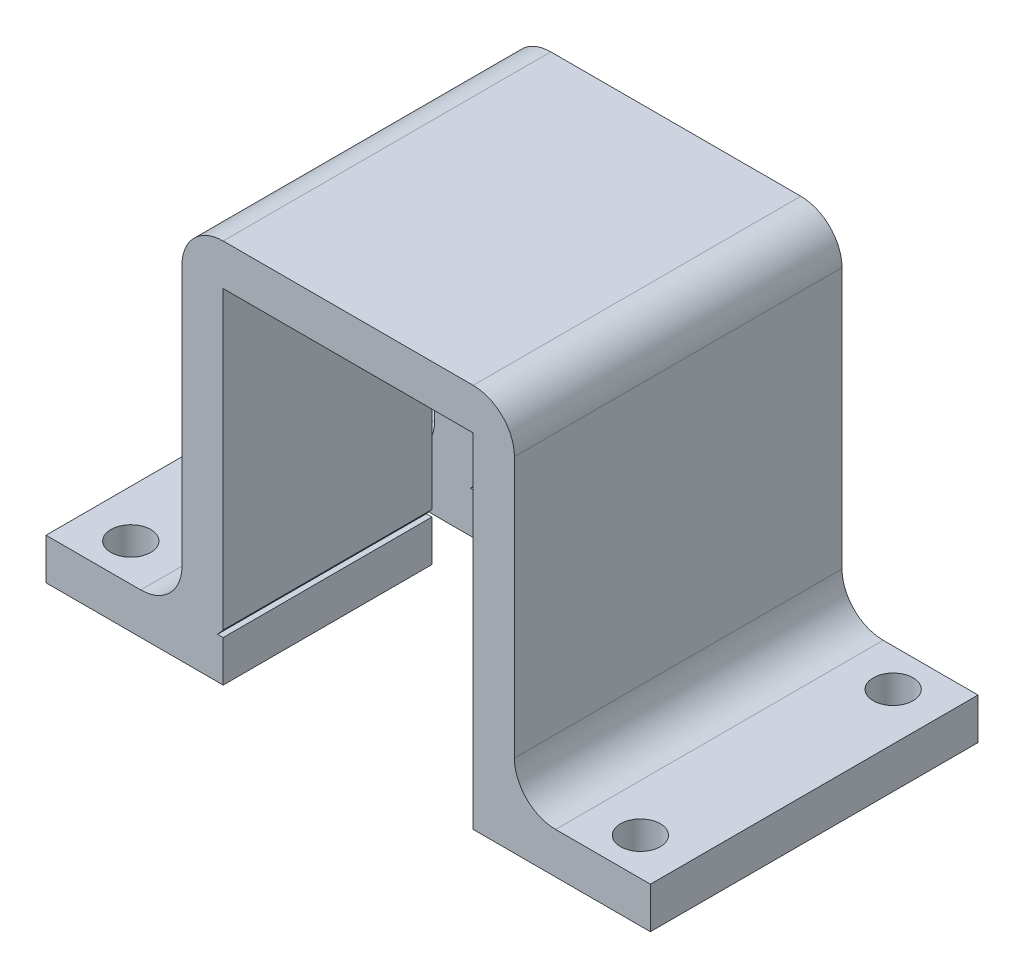
SolidWorks part; units mm, degrees
ref_plane "Front Plane" through (0, 0, 0) normal (0, 0, 1) x (1, 0, 0)
ref_plane "Top Plane" through (0, 0, 0) normal (0, 1, 0) x (1, 0, 0)
ref_plane "Right Plane" through (0, 0, 0) normal (1, 0, 0) x (0, 0, -1)
sketch "Sketch1" plane through (0, 0, 0) normal (0, 0, 1) x (1, 0, 0)
  line L1 (-9.1, 11) -> (9.1, 11)
  line L2 (-9.1, 11) -> (-9.1, -11)
  line L4 (9.1, 11) -> (9.1, -11)
  line L7 (-9.1, 14) -> (9.1, 14)
  line L8 (-12.1, 11) -> (-12.1, -8)
  line L9 (-12.1, -14) -> (-9.1, -14)
  line L10 (12.1, 11) -> (12.1, -8)
  line L12 (-9.1, -11) -> (-9.1, -14)
  line L13 (-22, -11) -> (-15.1, -11)
  line L14 (-22, -11) -> (-22, -14)
  line L15 (-22, -14) -> (-9.1, -14)
  line L16 (22, -11) -> (22, -14)
  line L17 (9.1, -11) -> (9.1, -14)
  line L18 (9.1, -14) -> (12.1, -14)
  line L19 (-9.5071, -11) -> (-9.1, -11)
  line L20 (-9.5071, -11) -> (-9.1, -10.5289) construction
  line L21 (15.1, -11) -> (22, -11)
  line L22 (9.1, -14) -> (22, -14)
  arc A0 (-9.1, 14) -> (-12.1, 11) centre (-9.1, 11) ccw
  arc A1 (9.1, 14) -> (12.1, 11) centre (9.1, 11) cw
  arc A2 (-12.1, -8) -> (-15.1, -11) centre (-15.1, -8) cw
  arc A3 (12.1, -8) -> (15.1, -11) centre (15.1, -8) ccw
  point P0 (0, 0)
  point P6 (0, 0)
  point P17 (0, -12.5)
  dimension "D5" = 3
  dimension "D9" = 3
  dimension "D1" = 22
  dimension "D2" = 18.2
  dimension "D3" = 3
  dimension "D4" = 3
  dimension "D6" = 3
  dimension "D7" = 44
  dimension "D8" = 14
  dimension "D10" = 3
  dimension "D11" = 9.9
  dimension "D12" = 9.9
  dimension "D13" = 9.1
  dimension "D14" = 9.1
extrude "Boss-Extrude1" add sketch "Sketch1" along normal blind 23.85 contours L19 L20 L2 L1 L4 L17 L18 L22 L16 L21 A3 L10 A1 L7 A0 L8 A2 L13 L14 L15 L9 L12
sketch "Sketch4" plane through (0, -11, 0) normal (0, 1, 0) x (1, 0, 0)
  line L0 (22, -11.925) -> (-22, -11.925) construction
  line L1 (22, -23.85) -> (22, 0) construction
  line L2 (-22, -23.85) -> (-22, 0) construction
  line L3 (0, -23.85) -> (0, 0) construction
  line L4 (-9.1, -23.85) -> (9.1, -23.85) construction
  circle A0 centre (-18.55, -21.125) radius 1.45
  circle A1 centre (-18.55, -2.725) radius 1.45
  circle A2 centre (18.55, -21.125) radius 1.45
  circle A3 centre (18.55, -2.725) radius 1.45
  dimension "D1" = 2.9
  dimension "D2" = 3.45
  dimension "D3" = 9.2
extrude "Cut-Extrude3" cut sketch "Sketch4" against normal blind 10
sketch "Sketch9" plane through (-12.1, 0, 0) normal (-1, 0, 0) x (0, 0, 1)
  line L0 (23.85, 1.5) -> (8.65, 1.5) construction
  line L1 (23.85, 11) -> (23.85, -8) construction
  line L2 (23.85, -14) -> (0, -14) construction
  line L3 (5.45, 6) -> (8.65, 6)
  line L4 (5.45, 6) -> (5.45, -14)
  line L5 (5.45, -14) -> (8.65, -14)
  line L6 (8.65, 6) -> (8.65, -14)
  point P8 (0, 0)
  dimension "D1" = 15.2
  dimension "D2" = 20
  dimension "D3" = 3.2
extrude "Cut-Extrude4" cut sketch "Sketch9" against normal blind 10 and the other way through all
